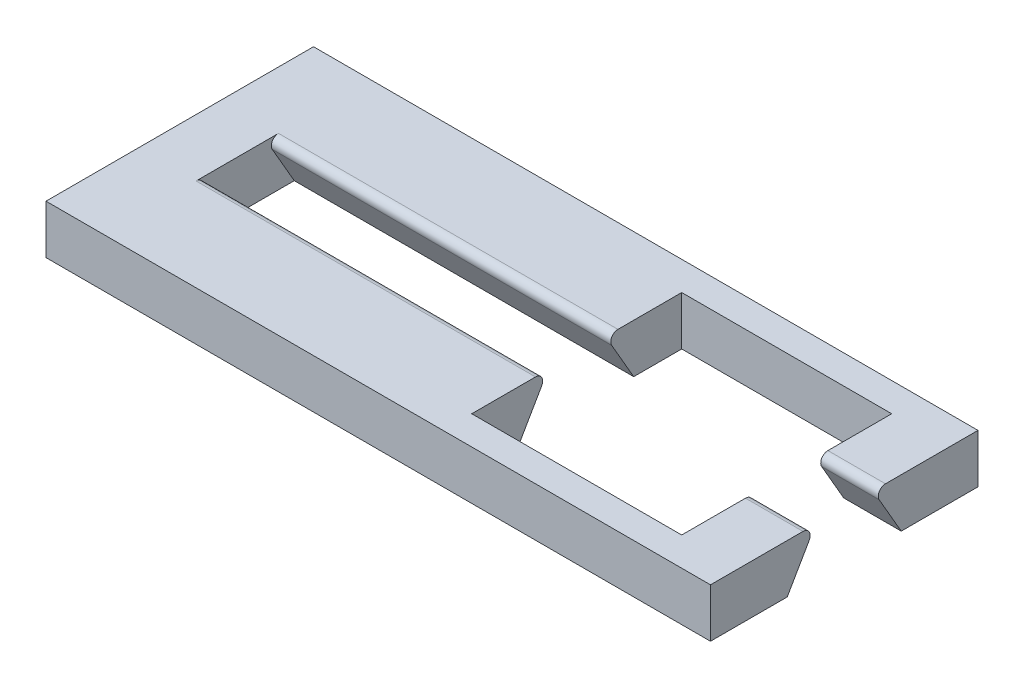
SolidWorks part; units mm, degrees
ref_plane "Front Plane" through (0, 0, 0) normal (0, 0, 1) x (1, 0, 0)
ref_plane "Top Plane" through (0, 0, 0) normal (0, 1, 0) x (1, 0, 0)
ref_plane "Right Plane" through (0, 0, 0) normal (1, 0, 0) x (0, 0, -1)
sketch "Sketch1" plane through (0, 0, 0) normal (0, 1, 0) x (1, 0, 0)
  line L1 (-23.1, -9.3) -> (23.1, -9.3)
  line L2 (-23.1, -9.3) -> (-23.1, 9.3)
  line L3 (-23.1, 9.3) -> (23.1, 9.3)
  line L4 (23.1, -9.3) -> (23.1, 9.3)
  line L5 (-23.1, -9.3) -> (23.1, 9.3) construction
  line L6 (-23.1, 9.3) -> (23.1, -9.3) construction
  point P0 (0, 0)
  dimension "D1" = 46.2
  dimension "D2" = 18.6
extrude "Boss-Extrude1" add sketch "Sketch1" along normal blind 3.4
sketch "Sketch2" plane through (23.1, 0, 0) normal (1, 0, 0) x (0, 0, -1)
  line L0 (2, 3.4) -> (-2, 3.4)
  line L1 (-9.3, 3.4) -> (9.3, 3.4) construction
  line L2 (-2, 3.4) -> (-3.963, 0)
  line L3 (-9.3, 0) -> (9.3, 0) construction
  line L4 (-3.963, 0) -> (3.963, 0)
  line L5 (0, 0) -> (0, 3.4) construction
  line L6 (2, 3.4) -> (3.963, 0)
  dimension "D1" = 60
  dimension "D2" = 2
extrude "Cut-Extrude1" cut sketch "Sketch2" against normal blind 42.2
sketch "Sketch3" plane through (0, 3.4, 0) normal (0, 1, 0) x (1, 0, 0)
  line L0 (-19.1, 2) -> (-19.1, -2) construction
  line L1 (19.1, 7.3) -> (4.5, 7.3)
  line L2 (19.1, 7.3) -> (19.1, -7.3)
  line L3 (19.1, -7.3) -> (4.5, -7.3)
  line L4 (4.5, 7.3) -> (4.5, -7.3)
  line L7 (23.1, 2) -> (23.1, 9.3) construction
  point P4 (4.5, 0)
  point P7 (-19.1, 0)
  dimension "D1" = 14.6
  dimension "D2" = 4
extrude "Cut-Extrude2" cut sketch "Sketch3" against normal through all
fillet "Fillet1" radius 0.5 4 edges at (21.1, 3.4, 2) (21.1, 3.4, -2) (-7.3, 3.4, 2) (-7.3, 3.4, -2)
